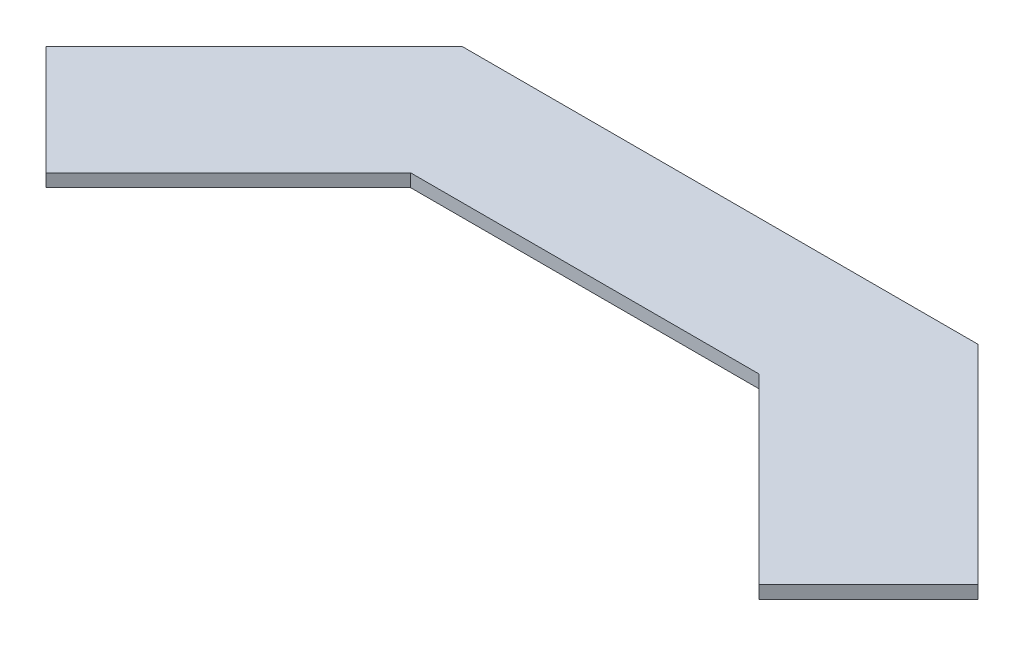
SolidWorks part; units mm, degrees
ref_plane "Front Plane" through (0, 0, 0) normal (0, 0, 1) x (1, 0, 0)
ref_plane "Top Plane" through (0, 0, 0) normal (0, 1, 0) x (1, 0, 0)
ref_plane "Right Plane" through (0, 0, 0) normal (1, 0, 0) x (0, 0, -1)
sketch "Sketch1" plane through (0, 0, 0) normal (0, 1, 0) x (1, 0, 0)
  line L0 (-139.7, 0) -> (139.7, 0) construction
  line L1 (-139.7, 0) -> (-202.5618, -62.8618) construction
  line L2 (0, -66.5815) -> (0, 66.5815) construction
  line L3 (-229.5026, -35.921) -> (-166.6408, 26.9408)
  line L4 (-229.5026, -35.921) -> (-175.621, -89.8026)
  line L5 (-166.6408, 26.9408) -> (-112.7592, -26.9408) construction
  line L6 (-175.621, -89.8026) -> (-85.8185, 0)
  line L7 (-229.5026, -35.921) -> (-112.7592, -26.9408) construction
  line L8 (-166.6408, 26.9408) -> (-175.621, -89.8026) construction
  line L10 (127, 66.5815) -> (-127, 66.5815)
  line L11 (-127, 66.5815) -> (-166.6408, 26.9408)
  line L14 (166.6408, 26.9408) -> (175.621, -89.8026) construction
  line L15 (229.5026, -35.921) -> (112.7592, -26.9408) construction
  line L16 (166.6408, 26.9408) -> (112.7592, -26.9408) construction
  line L17 (139.7, 0) -> (202.5618, -62.8618) construction
  line L18 (127, 66.5815) -> (166.6408, 26.9408)
  line L19 (175.621, -89.8026) -> (85.8185, 0)
  line L20 (229.5026, -35.921) -> (175.621, -89.8026)
  line L21 (229.5026, -35.921) -> (166.6408, 26.9408)
  line L23 (-85.8185, 0) -> (85.8185, 0)
  point P3 (-171.1309, -31.4309)
  point P4 (0, 0)
  point P9 (0, 0)
  point P10 (-139.7, 0)
  point P23 (171.1309, -31.4309)
  dimension "D1" = 279.4
  dimension "D2" = 254
  dimension "D3" = 135
  dimension "D4" = 88.9
  dimension "D5" = 76.2
extrude "Boss-Extrude1" add sketch "Sketch1" along normal blind 6.35
